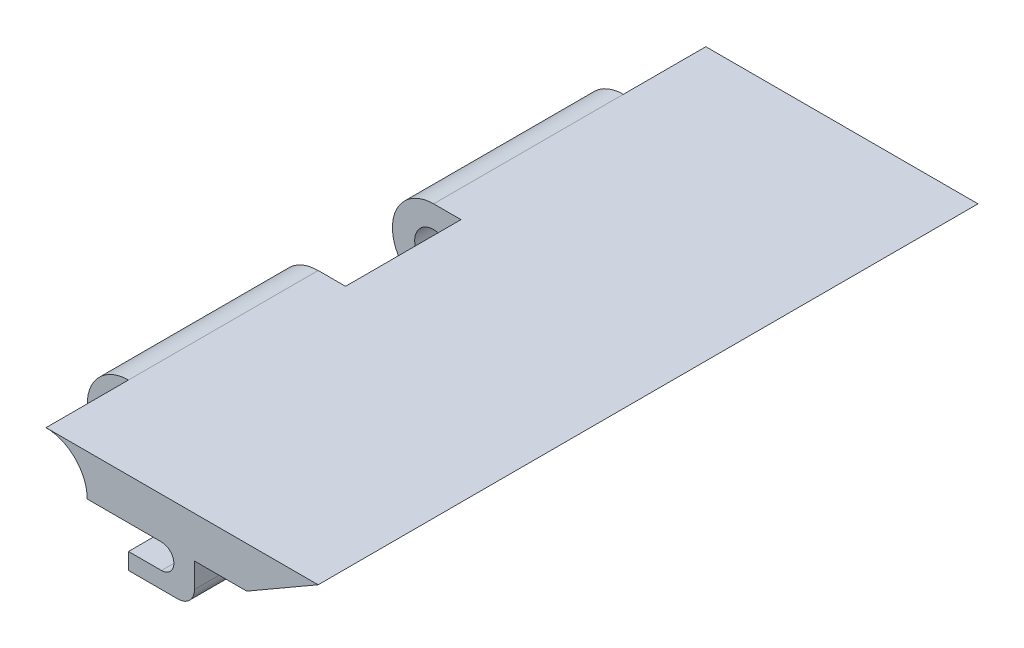
SolidWorks part; units mm, degrees
ref_plane "前视基准面" through (0, 0, 0) normal (0, 0, 1) x (1, 0, 0)
ref_plane "上视基准面" through (0, 0, 0) normal (0, 1, 0) x (1, 0, 0)
ref_plane "右视基准面" through (0, 0, 0) normal (1, 0, 0) x (0, 0, -1)
other "Configuration Table"
sketch "草图1" plane through (0, 0, 0) normal (0, 0, 1) x (1, 0, 0)
  line L0 (-2.5, 0) -> (-2.5, -50000) construction
  line L1 (2.5, 0) -> (12.1699, 0)
  line L2 (12.1699, 0) -> (16.5, 2.5)
  line L3 (16.5, 2.5) -> (0, 2.5)
  arc A0 (0, 2.5) -> (2.5, 0) centre (0, 0) ccw
  circle A1 centre (0, 0) radius 1.15
  dimension "D1" = 5
  dimension "D3" = 2.3
  dimension "D2" = 19
  dimension "D4" = 30
extrude "凸台-拉伸1" add sketch "草图1" along normal mid plane 40
sketch "草图4" plane through (0, 0, 0) normal (0, 0, 1) x (1, 0, 0)
  line L1 (2.5, 0) -> (12.1699, 0) construction
  line L2 (7, -1.5) -> (5, -1.5)
  line L3 (5, -1.5) -> (5, -2.5)
  line L4 (5, -2.5) -> (8, -2.5)
  line L5 (9, -1.5) -> (9, 0)
  line L7 (7, 0) -> (9, 0)
  arc A0 (7, 0) -> (7, -1.5) centre (7, -0.75) cw
  arc A1 (9, -1.5) -> (8, -2.5) centre (8, -1.5) cw
  dimension "D6" = 0.75
  dimension "D7" = 1
  dimension "D1" = 1.5
  dimension "D2" = 5
  dimension "D3" = 2
  dimension "D4" = 4
  dimension "D5" = 1
extrude "凸台-拉伸2" add sketch "草图4" along normal mid plane 40
sketch "草图5" plane through (0, 0, 0) normal (0, 0, 1) x (1, 0, 0)
  circle A0 centre (0, 0) radius 3
  dimension "D1" = 6
extrude "切除-拉伸2" cut sketch "草图5" against normal mid plane 7
sketch "草图6" plane through (0, 0, -20) normal (0, 0, -1) x (-1, 0, 0)
  circle A0 centre (0, 0) radius 2.5
sketch "草图7" plane through (0, 0, 20) normal (0, 0, 1) x (1, 0, 0)
  circle A0 centre (0, 0) radius 2.5
extrude "切除-拉伸3" cut sketch "草图6" against normal blind 5
extrude "切除-拉伸4" cut sketch "草图7" against normal blind 5
sketch "草图10" plane through (0, 0, 0) normal (0, -1, 0) x (1, 0, 0)
  line L0 (12.1699, 20) -> (12.1699, -20) construction
  line L1 (12.1699, -15) -> (2.5, -15)
  line L2 (12.1699, -15) -> (12.1699, -12)
  line L3 (12.1699, -12) -> (2.5, -12)
  line L4 (2.5, -15) -> (2.5, -12)
  line L5 (2.5, -3.5) -> (2.5, -15) construction
  line L6 (2.5, 15) -> (2.5, 3.5) construction
  line L7 (12.1699, 12) -> (2.5, 12)
  line L8 (12.1699, 12) -> (12.1699, 15)
  line L9 (12.1699, 15) -> (2.5, 15)
  line L10 (2.5, 12) -> (2.5, 15)
  line L11 (9, 20) -> (12.1699, 20) construction
  line L12 (9, -20) -> (12.1699, -20) construction
  dimension "D1" = 5
  dimension "D2" = 3
  dimension "D3" = 3
  dimension "D4" = 5
extrude "切除-拉伸5" cut sketch "草图10" along normal blind 3
